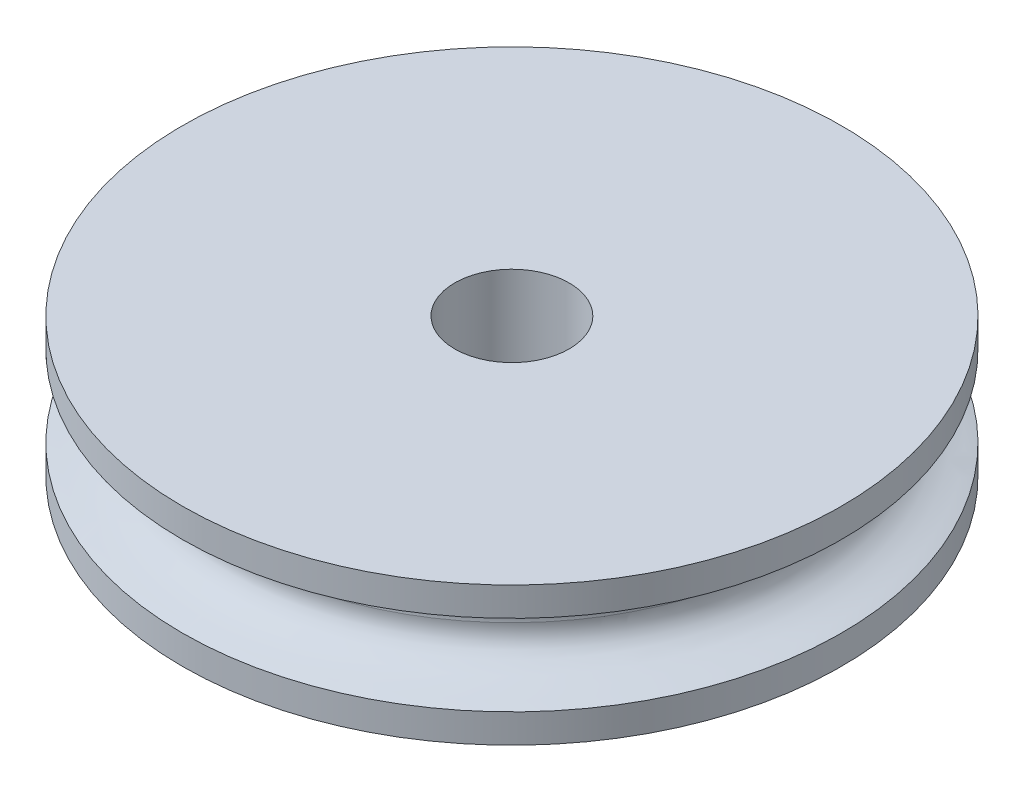
SolidWorks part; units mm, degrees
ref_plane "Front Plane" through (0, 0, 0) normal (0, 0, 1) x (1, 0, 0)
ref_plane "Top Plane" through (0, 0, 0) normal (0, 1, 0) x (1, 0, 0)
ref_plane "Right Plane" through (0, 0, 0) normal (1, 0, 0) x (0, 0, -1)
sketch "Sketch1" plane through (0, 0, 0) normal (0, 1, 0) x (1, 0, 0)
  circle A0 centre (0, 0) radius 9.5
extrude "Boss-Extrude1" add sketch "Sketch1" along normal blind 4
sketch "Sketch2" plane through (0, 0, 0) normal (0, 0, 1) x (1, 0, 0)
  line L0 (-9.5, 0) -> (9.5, 0) construction
  line L1 (9.5, 4) -> (-9.5, 4) construction
  line L2 (-9.5, 0) -> (9.5, 0) construction
  line L3 (9.5, 4) -> (-9.5, 4) construction
  line L4 (-9.5, 4) -> (-9.5, 0) construction
  line L5 (9.5, 0) -> (9.5, 4) construction
  line L6 (-9.5, 4) -> (-9.5, 0) construction
  line L7 (9.5, 0) -> (9.5, 4) construction
  line L8 (-9.5, 2) -> (9.5, 2) construction
  line L9 (-9.5, 4) -> (-9.5, 3.1672)
  line L10 (-9.5, 0) -> (-9.5, 0.8328)
  line L11 (-9.5, 3.1672) -> (-9.5, 0.8328)
  spline S0 degree 3 poles (-9.5, 3.1672) (-8.911, 2.9848) (-7.9402, 2.8431) (-8, 2) knots 0 0 0 0 1 1 1 1
  spline S1 degree 3 poles (-9.5, 0.8328) (-8.911, 1.0152) (-7.9402, 1.1569) (-8, 2) knots 0 0 0 0 1 1 1 1
  point P6 (-8, 2)
  point P10 (-10.6735, 2.075)
  point P12 (-8, 2)
  point P16 (0, 0)
  dimension "D1" = 1.5
ref_axis "Revolving cut axis" through (0, 4.2, 0) along (0, -1, 0)
revolve "Cut-Revolve3" cut sketch "Sketch2" angle 360 about axis through (0, 4.2, 0) along (0, -1, 0)
sketch "Sketch3" plane through (0, 4, 0) normal (0, 1, 0) x (1, 0, 0)
  circle A0 centre (0, 0) radius 1.65
extrude "Cut-Extrude1" cut sketch "Sketch3" against normal through all
sketch "Sketch4" plane through (0, 4, 0) normal (0, 1, 0) x (1, 0, 0)
  circle A2 centre (0, 0) radius 11
  circle A3 centre (0, 0) radius 11
  circle A4 centre (0, 0) radius 1.65
  circle A5 centre (0, 0) radius 1.65
  dimension "D1" = 1.5
  dimension "D2" = 0
ref_point "Extension top point" [suppressed]
extrude "Extension top" [suppressed] add sketch "Sketch4" against normal up to vertex
sketch "Sketch5" plane through (0, 0, 0) normal (0, -1, 0) x (1, 0, 0)
  circle A2 centre (0, 0) radius 1.65
  circle A3 centre (0, 0) radius 1.65
  circle A5 centre (0, 0) radius 11.5
  circle A6 centre (0, 0) radius 11.5
  dimension "D1" = 0
  dimension "D2" = 2
ref_point "Extension bottom point" [suppressed]
extrude "Boss-Extrude4" [suppressed] add sketch "Sketch5" against normal up to vertex
